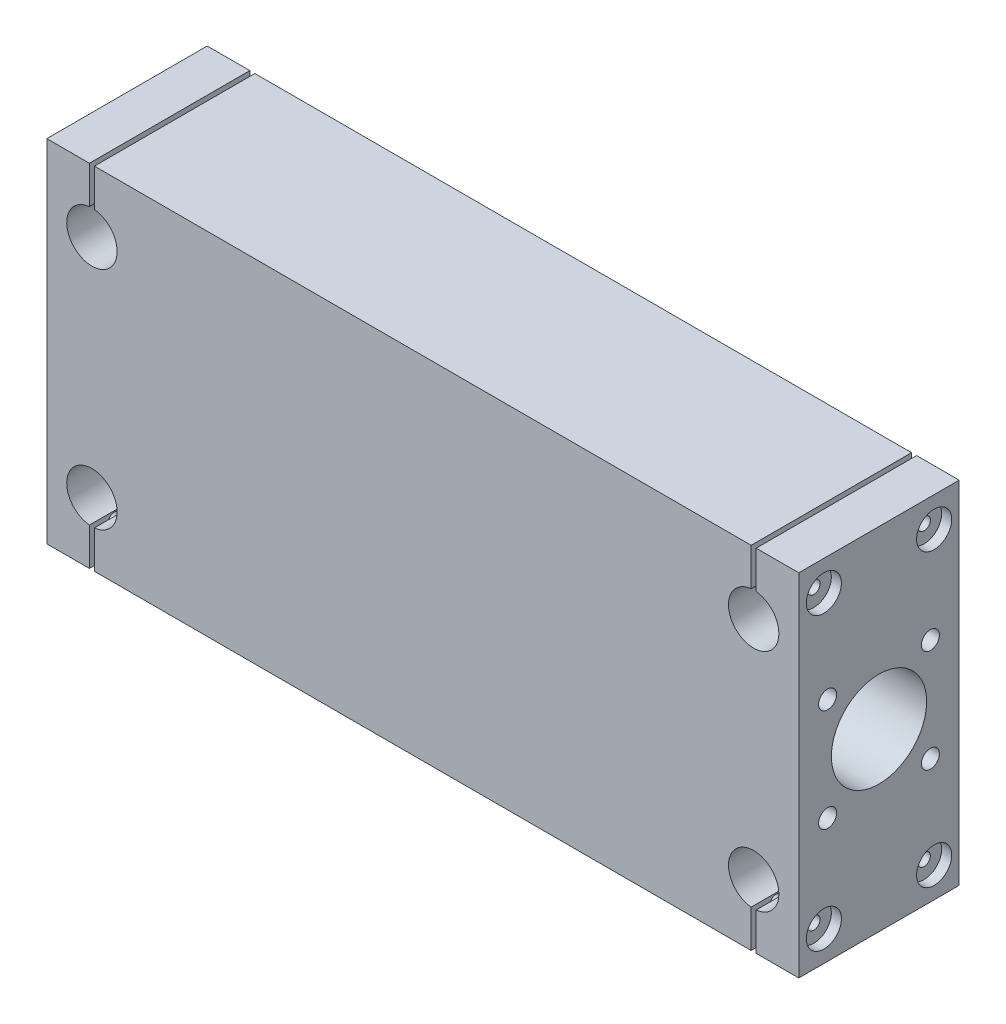
SolidWorks part; units mm, degrees
material "1060 Alloy"
ref_plane "Front Plane" through (0, 0, 0) normal (0, 0, 1) x (1, 0, 0)
ref_plane "Top Plane" through (0, 0, 0) normal (0, 1, 0) x (1, 0, 0)
ref_plane "Right Plane" through (0, 0, 0) normal (1, 0, 0) x (0, 0, -1)
sketch "Sketch1" plane through (0, 0, 0) normal (0, 0, 1) x (1, 0, 0)
  line L1 (-150, 0) -> (0, 0)
  line L2 (-150, 0) -> (-150, -70)
  line L3 (-150, -70) -> (0, -70)
  line L4 (0, 0) -> (0, -70)
  dimension "D1" = 150
  dimension "D2" = 70
extrude "Boss-Extrude1" add sketch "Sketch1" along normal blind 32
sketch "Sketch2" plane through (-150, 0, 0) normal (-1, 0, 0) x (0, 0, 1)
  line L0 (16, 0) -> (16, -70) construction
  line L1 (32, 0) -> (0, 0) construction
  line L2 (32, -70) -> (0, -70) construction
  line L3 (0, -35) -> (32, -35) construction
  line L4 (0, 0) -> (0, -70) construction
  line L5 (32, 0) -> (32, -70) construction
  circle A0 centre (16, -35) radius 9.5
  dimension "D1" = 19
extrude "Linear_bearing-cut-1" cut sketch "Sketch2" against normal blind 55
sketch "Sketch5" plane through (0, 0, 32) normal (0, 0, 1) x (1, 0, 0)
  line L0 (-75, 0) -> (-75, -70) construction
  line L1 (0, 0) -> (-150, 0) construction
  line L2 (-150, -70) -> (0, -70) construction
  line L3 (0, -35) -> (-150, -35) construction
  line L4 (0, -70) -> (0, 0) construction
  line L5 (-150, 0) -> (-150, -70) construction
  line L6 (-141, 0) -> (-141, -12.5) construction
  line L7 (-141, -12.5) -> (-9, -12.5) construction
  line L8 (-9, -12.5) -> (-9, 0) construction
  line L9 (-9, -57.5) -> (-9, -70) construction
  line L10 (-141, -57.5) -> (-9, -57.5) construction
  line L11 (-141, -70) -> (-141, -57.5) construction
  line L12 (-141.5, 0) -> (-141.5, -7.5)
  line L13 (-140.5, 0) -> (-140.5, -7.5)
  line L14 (-8.5, 0) -> (-8.5, -7.5)
  line L15 (-9.5, 0) -> (-9.5, -7.5)
  line L16 (-141.5, -70) -> (-141.5, -62.5)
  line L17 (-140.5, -70) -> (-140.5, -62.5)
  line L18 (-9.5, -70) -> (-9.5, -62.5)
  line L19 (-8.5, -70) -> (-8.5, -62.5)
  line L20 (-141.5, 0) -> (-140.5, 0)
  line L21 (-9.5, 0) -> (-8.5, 0)
  line L22 (-9.5, -70) -> (-8.5, -70)
  line L23 (-141.5, -70) -> (-140.5, -70)
  arc A0 (-141.5, -7.5) -> (-140.5, -7.5) centre (-141, -12.5) ccw
  arc A1 (-8.5, -7.5) -> (-9.5, -7.5) centre (-9, -12.5) cw
  arc A2 (-141.5, -62.5) -> (-140.5, -62.5) centre (-141, -57.5) cw
  arc A3 (-8.5, -62.5) -> (-9.5, -62.5) centre (-9, -57.5) ccw
  dimension "D1" = 9
  dimension "D3" = 12.5
  dimension "D5" = 0.5
  dimension "D6" = 7.5
extrude "Y-axis-shafts-cut" cut sketch "Sketch5" against normal through all
sketch "Sketch6" plane through (-95, 0, 0) normal (-1, 0, 0) x (0, 0, 1)
  line L0 (16, -25.5) -> (16, -44.5) construction
  circle A0 centre (16, -35) radius 9.5 construction
  circle A1 centre (16, -35) radius 9.5 construction
  circle A2 centre (16, -35) radius 6
  dimension "D1" = 12
sketch "Sketch7" plane through (0, 0, 0) normal (1, 0, 0) x (0, 0, -1)
  circle A0 centre (-16, -35) radius 9.5
  dimension "D1" = 19
extrude "Linear-bearing-cut-2" cut sketch "Sketch7" against normal blind 55
extrude "between-bearings" cut sketch "Sketch6" against normal through all
sketch "Sketch8" plane through (-150, 0, 0) normal (-1, 0, 0) x (0, 0, 1)
  line L0 (5, 0) -> (5, -6) construction
  line L1 (32, 0) -> (0, 0) construction
  line L2 (5, -6) -> (27, -6) construction
  line L3 (27, -6) -> (27, 0) construction
  line L4 (0, 0) -> (0, -70) construction
  line L5 (32, 0) -> (32, -70) construction
  line L6 (16, 0) -> (16, -70) construction
  line L7 (32, -70) -> (0, -70) construction
  line L8 (0, -35) -> (32, -35) construction
  line L9 (5, -39.9148) -> (4.7174, -39.9148) construction
  circle A0 centre (5, -6) radius 3.5
  circle A1 centre (27, -6) radius 3.5
  circle A2 centre (27, -64) radius 3.5
  circle A3 centre (5, -64) radius 3.5
  dimension "D4" = 7
  dimension "D1" = 5
  dimension "D3" = 6
extrude "shaft-holder-screw-cut" cut sketch "Sketch8" against normal blind 4
sketch "Sketch9" plane through (-146, 0, 0) normal (-1, 0, 0) x (0, 0, 1)
  line L0 (5, -2.5) -> (5, -9.5) construction
  line L1 (27, -2.5) -> (27, -9.5) construction
  line L2 (27, -60.5) -> (27, -67.5) construction
  line L3 (5, -60.5) -> (5, -67.5) construction
  circle A0 centre (5, -6) radius 3.5 construction
  circle A1 centre (5, -6) radius 3.5 construction
  circle A2 centre (27, -6) radius 3.5 construction
  circle A3 centre (27, -6) radius 3.5 construction
  circle A4 centre (27, -64) radius 3.5 construction
  circle A5 centre (27, -64) radius 3.5 construction
  circle A6 centre (5, -64) radius 3.5 construction
  circle A7 centre (5, -64) radius 3.5 construction
  circle A8 centre (5, -6) radius 1.25
  circle A9 centre (27, -6) radius 1.25
  circle A10 centre (5, -64) radius 1.25
  circle A11 centre (27, -64) radius 1.25
  dimension "D1" = 2.5
extrude "shaft-holder-screw-cut2" cut sketch "Sketch9" against normal blind 20
sketch "Sketch10" plane through (0, 0, 0) normal (1, 0, 0) x (0, 0, -1)
  line L0 (-27, 0) -> (-27, -6) construction
  line L1 (-32, 0) -> (0, 0) construction
  line L2 (-27, -6) -> (-5, -6) construction
  line L3 (-5, -6) -> (-5, 0) construction
  line L4 (-32, -70) -> (-32, 0) construction
  line L5 (0, -70) -> (0, 0) construction
  line L6 (-16, 0) -> (-16, -70) construction
  line L7 (-32, -70) -> (0, -70) construction
  line L8 (-32, -35) -> (0, -35) construction
  circle A0 centre (-27, -6) radius 3.5
  circle A1 centre (-5, -6) radius 3.5
  circle A2 centre (-5, -64) radius 3.5
  circle A3 centre (-27, -64) radius 3.5
  dimension "D4" = 7
  dimension "D1" = 5
  dimension "D2" = 6
extrude "shaft-holder-screw-cut-3" cut sketch "Sketch10" against normal blind 2
sketch "Sketch11" plane through (-2, 0, 0) normal (1, 0, 0) x (0, 0, -1)
  line L0 (-27, -2.5) -> (-27, -9.5) construction
  line L1 (-5, -2.5) -> (-5, -9.5) construction
  line L2 (-5, -60.5) -> (-5, -67.5) construction
  line L3 (-27, -60.5) -> (-27, -67.5) construction
  circle A0 centre (-27, -6) radius 3.5 construction
  circle A1 centre (-27, -6) radius 3.5 construction
  circle A2 centre (-5, -6) radius 3.5 construction
  circle A3 centre (-5, -6) radius 3.5 construction
  circle A4 centre (-5, -64) radius 3.5 construction
  circle A5 centre (-5, -64) radius 3.5 construction
  circle A6 centre (-27, -64) radius 3.5 construction
  circle A7 centre (-27, -64) radius 3.5 construction
  circle A8 centre (-27, -6) radius 1.25
  circle A9 centre (-5, -6) radius 1.25
  circle A10 centre (-5, -64) radius 1.25
  circle A11 centre (-27, -64) radius 1.25
  dimension "D1" = 2.5
extrude "shaft-holder-screw-cut-4" cut sketch "Sketch11" against normal blind 20
sketch "Sketch12" plane through (0, 0, 0) normal (1, 0, 0) x (0, 0, -1)
  line L0 (-5.75, 0) -> (-5.75, -24.75) construction
  line L1 (-32, 0) -> (0, 0) construction
  line L2 (-5.75, -24.75) -> (0, -24.75) construction
  line L3 (0, -70) -> (0, 0) construction
  line L4 (-16, 0) -> (-16, -70) construction
  line L5 (-32, -70) -> (0, -70) construction
  line L6 (0, -35) -> (-32, -35) construction
  line L7 (-32, -70) -> (-32, 0) construction
  circle A0 centre (-5.75, -24.75) radius 1.8
  circle A1 centre (-26.25, -24.75) radius 1.8
  circle A2 centre (-5.75, -45.25) radius 1.8
  circle A3 centre (-26.25, -45.25) radius 1.8
  dimension "D3" = 3.6
  dimension "D1" = 5.75
  dimension "D2" = 24.75
extrude "Linear-bearing-srew1" cut sketch "Sketch12" against normal blind 14
sketch "Sketch13" plane through (-150, 0, 0) normal (-1, 0, 0) x (0, 0, 1)
  line L0 (27.5, 0) -> (27.5, -24.75) construction
  line L1 (32, 0) -> (0, 0) construction
  line L2 (27.5, -24.75) -> (32, -24.75) construction
  line L3 (32, 0) -> (32, -70) construction
  line L4 (16, 0) -> (16, -70) construction
  line L5 (32, -70) -> (0, -70) construction
  line L6 (32, -35) -> (0, -35) construction
  line L7 (0, 0) -> (0, -70) construction
  circle A0 centre (27.5, -24.75) radius 1.85
  circle A1 centre (4.5, -24.75) radius 1.85
  circle A2 centre (27.5, -45.25) radius 1.85
  circle A3 centre (4.5, -45.25) radius 1.85
  dimension "D3" = 3.7
  dimension "D1" = 24.75
  dimension "D2" = 4.5
extrude "Linear-bearing-screw2" cut sketch "Sketch13" against normal blind 14
